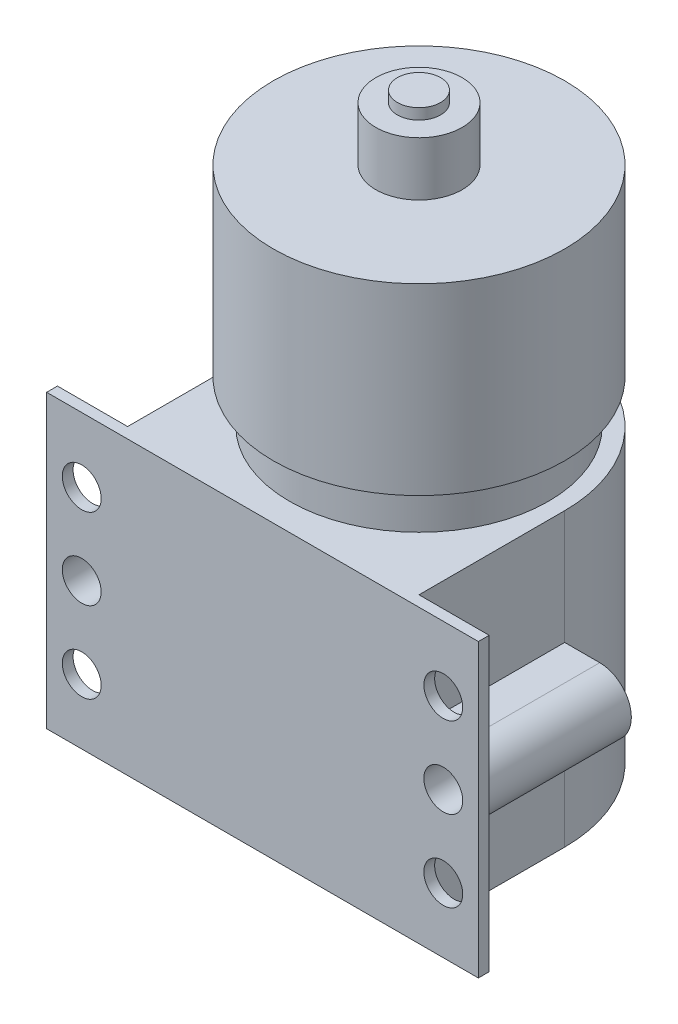
SolidWorks part; units mm, degrees
ref_plane "正面" through (0, 0, 0) normal (0, 0, 1) x (1, 0, 0)
ref_plane "平面" through (0, 0, 0) normal (0, 1, 0) x (1, 0, 0)
ref_plane "右側面" through (0, 0, 0) normal (1, 0, 0) x (0, 0, -1)
sketch "ｽｹｯﾁ1" plane through (0, 0, 0) normal (0, 1, 0) x (1, 0, 0)
  line L0 (0, -13.5) -> (20, -13.5)
  line L1 (0, -13.5) -> (-20, -13.5)
  line L2 (-13.5, 0) -> (-13.5, -13.5)
  line L3 (13.5, 0) -> (13.5, -13.5)
  line L5 (-20, -13.5) -> (20, -13.5)
  line L6 (-20, -13.5) -> (-20, -14.5)
  line L7 (-20, -14.5) -> (20, -14.5)
  line L8 (20, -13.5) -> (20, -14.5)
  circle A0 centre (0, 0) radius 13.5
extrude "ﾎﾞｽ - 押し出し7" add sketch "ｽｹｯﾁ1" along normal blind 27 contours A0 | A0 L2 L1 | A0 L0 L3 | L8 L0 L1 L6 L7
sketch "ｽｹｯﾁ2" plane through (0, 0, 13.5) normal (0, 0, -1) x (-1, 0, 0)
  line L0 (16.75, 10.575) -> (13.5, 10.575)
  line L1 (13.5, 27) -> (13.5, 0) construction
  line L4 (16.75, 16.425) -> (13.5, 16.425)
  circle A0 centre (16.75, 13.5) radius 2.925
  line M4 (13.5, 27) -> (13.5, 0)
extrude "ﾎﾞｽ - 押し出し9" add sketch "ｽｹｯﾁ2" along normal blind 13.5 contours A0 | A0 L0 M4
sketch "ｽｹｯﾁ3" plane through (0, 0, 13.5) normal (0, 0, -1) x (-1, 0, 0)
  line L0 (-16.75, 10.575) -> (-13.5, 10.575)
  line L1 (-13.5, 27) -> (-13.5, 0) construction
  line L2 (-16.75, 16.425) -> (-13.5, 16.425)
  circle A0 centre (-16.75, 13.5) radius 2.925
  line M3 (-13.5, 0) -> (-13.5, 27)
extrude "ﾎﾞｽ - 押し出し10" add sketch "ｽｹｯﾁ3" along normal blind 13.5 contours A0 L0 M3 | A0
sketch "ｽｹｯﾁ9" plane through (0, 0, 0) normal (0, -1, 0) x (1, 0, 0)
  circle A0 centre (0, 0) radius 12
extrude "ﾎﾞｽ - 押し出し11" add sketch "ｽｹｯﾁ9" against normal blind 4 from offset 27 offset against normal yes
sketch "ｽｹｯﾁ10" plane through (0, 0, 0) normal (0, -1, 0) x (1, 0, 0)
  circle A0 centre (0, 0) radius 13.5
extrude "ﾎﾞｽ - 押し出し12" add sketch "ｽｹｯﾁ10" against normal blind 17 from offset 31 offset against normal yes
sketch "ｽｹｯﾁ11" plane through (0, 0, 0) normal (0, -1, 0) x (1, 0, 0)
  circle A0 centre (0, 0) radius 4
sketch "ｽｹｯﾁ12" plane through (0, 0, 0) normal (0, -1, 0) x (1, 0, 0)
  circle A0 centre (0, 0) radius 2
extrude "ﾎﾞｽ - 押し出し13" add sketch "ｽｹｯﾁ11" against normal blind 5 from offset 48 offset against normal yes
extrude "ﾎﾞｽ - 押し出し14" add sketch "ｽｹｯﾁ12" against normal blind 1 from offset 53 offset against normal yes
hole_wizard "M3 すきま穴1" positions "3Dｽｹｯﾁ1" profile "ｽｹｯﾁ13" hole size "M3" standard "JIS" end condition through all
sketch3d "3Dｽｹｯﾁ1"
  line L0 (13.5, 27, 13.5) -> (20, 27, 13.5) construction
  line L1 (20, 27, 13.5) -> (20, 0, 13.5) construction
  line L2 (13.5, 0, 13.5) -> (20, 0, 13.5) construction
  line L3 (-20, 27, 13.5) -> (-20, 0, 13.5) construction
  line L4 (-20, 0, 13.5) -> (-13.5, 0, 13.5) construction
  line L5 (-20, 27, 13.5) -> (-13.5, 27, 13.5) construction
  line L6 (-16.75, 16.425, 0) -> (-13.5, 16.425, 0) construction
  line L7 (-13.5, 16.425, 0) -> (-13.5, 10.575, 0) construction
  line L8 (13.5, 10.575, 0) -> (13.5, 16.425, 0) construction
  line L9 (16.75, 10.575, 0) -> (13.5, 10.575, 0) construction
  point P0 (16.75, 21, 13.5)
  point P2 (16.75, 13.5, 0)
  point P4 (16.75, 6, 13.5)
  point P6 (-16.75, 21, 13.5)
  point P8 (-16.75, 6, 13.5)
  point P10 (-16.75, 13.5, 0)
  dimension "D1" = 6
  dimension "D2" = 3.25
  dimension "D3" = 6
  dimension "D4" = 3.25
  dimension "D5" = 3.25
  dimension "D6" = 6
  dimension "D7" = 6
  dimension "D8" = 3.25
  dimension "D9" = 2.925
  dimension "D10" = 3.25
  dimension "D11" = 3.25
  dimension "D12" = 2.925
sketch "ｽｹｯﾁ13" plane through (16.75, 21, 13.5) normal (1, 0, 0) x (0, 1, 0)
  line L0 (0, 0) -> (0, 1)
  line L1 (0, 1) -> (1.8, 1)
  line L2 (1.8, 1) -> (1.8, 0)
  line L5 (1.8, 0) -> (0, 0)
  line L11 (0, -6.35) -> (0, 107.95) construction
  dimension "通し穴の直径" = 3.6
  dimension "通し穴の深さ" = 1
hole_wizard "M3 すきま穴2" positions "ｽｹｯﾁ14" profile "ｽｹｯﾁ15"
sketch "ｽｹｯﾁ14" plane through (-107.7057, -169.1337, 14.5) normal (0, 0, -1) x (-1, 0, 0)
  point P0 (-123.939, 0.1366)
  point P2 (-124.4557, 7.6337)
  point P5 (-124.4557, 15.1337)
  point P8 (-90.9557, 0.1337)
  point P11 (-90.9557, 7.6337)
  point P14 (-90.9557, 15.1337)
  point P17 (-124.4557, 175.137)
  point P19 (-124.4557, 190.1337)
  point P22 (-90.9557, 175.1337)
  point P25 (-90.9557, 182.6337)
  point P28 (-91.5292, 190.1337)
  point P31 (-124.4557, 182.6337)
sketch "ｽｹｯﾁ15" plane through (16.2333, -168.997, 14.5) normal (1, 0, 0) x (0, 1, 0)
  line L0 (0, 0) -> (0, 3.0215)
  line L1 (0, 3.0215) -> (1.7, 2)
  line L2 (1.7, 2) -> (1.7, 0)
  line L3 (1.7, 0) -> (0, 0)
  line L4 (0, 3.0215) -> (-1.7, 2) construction
  line L5 (0, -6.35) -> (0, 107.95) construction
  dimension "穴の直径" = 3.4
  dimension "穴の深さ" = 2
  dimension "ﾄﾞﾘﾙ角度" = 118
hole_wizard "M3 すきま穴3" positions "ｽｹｯﾁ16" profile "ｽｹｯﾁ17"
sketch "ｽｹｯﾁ16" plane through (107.7057, 21.1337, 14.5) normal (0, 0, -1) x (1, 0, 0)
  point P0 (-123.939, 0.1366)
  point P2 (-124.4557, 7.6337)
  point P5 (-124.4557, 15.1337)
  point P8 (-90.9557, 0.1337)
  point P11 (-90.9557, 7.6337)
  point P14 (-90.9557, 15.1337)
  point P17 (-124.4557, 175.137)
  point P19 (-124.4557, 190.1337)
  point P22 (-90.9557, 175.1337)
  point P25 (-90.9557, 182.6337)
  point P28 (-91.5292, 190.1337)
  point P31 (-124.4557, 182.6337)
sketch "ｽｹｯﾁ17" plane through (-16.2333, 20.997, 14.5) normal (1, 0, 0) x (0, 1, 0)
  line L0 (0, 0) -> (0, 3.0215)
  line L1 (0, 3.0215) -> (1.7, 2)
  line L2 (1.7, 2) -> (1.7, 0)
  line L3 (1.7, 0) -> (0, 0)
  line L4 (0, 3.0215) -> (-1.7, 2) construction
  line L5 (0, -6.35) -> (0, 107.95) construction
  dimension "穴の直径" = 3.4
  dimension "穴の深さ" = 2
  dimension "ﾄﾞﾘﾙ角度" = 118
